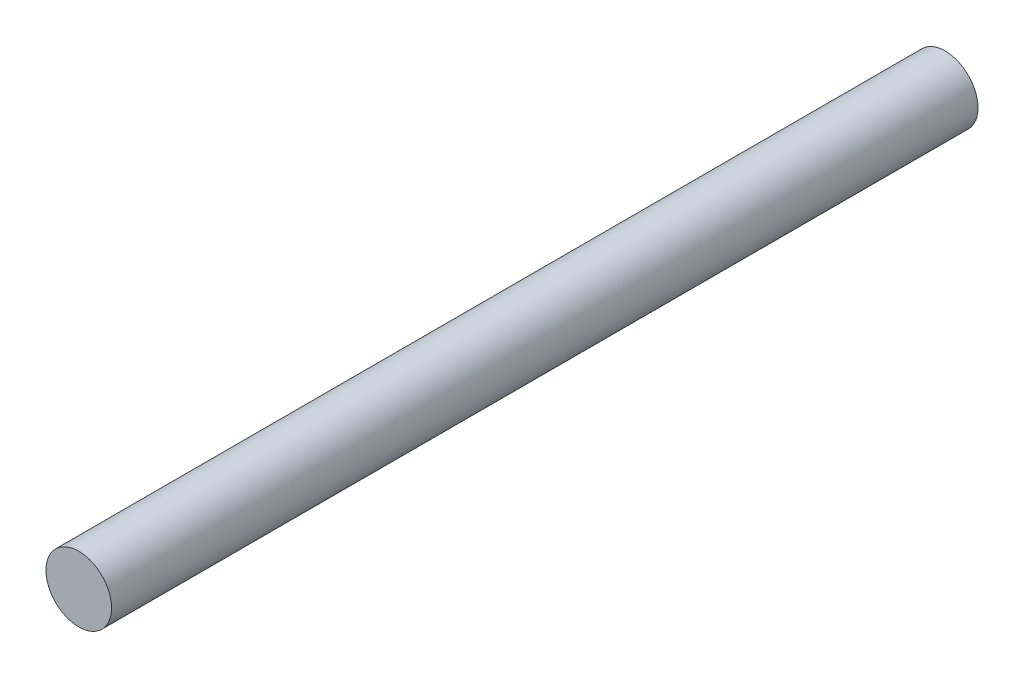
SolidWorks part; units mm, degrees
ref_plane "Front Plane" through (0, 0, 0) normal (0, 0, 1) x (1, 0, 0)
ref_plane "Top Plane" through (0, 0, 0) normal (0, 1, 0) x (1, 0, 0)
ref_plane "Right Plane" through (0, 0, 0) normal (1, 0, 0) x (0, 0, -1)
sketch "Sketch1" plane through (0, 0, 0) normal (0, 0, 1) x (1, 0, 0)
  circle A0 centre (0, 0) radius 2.5
  dimension "D1" = 5
extrude "Boss-Extrude1" add sketch "Sketch1" along normal blind 66
ref_point "Centre"
equation "\"StrutWidth\"= 15"
equation "\"D1@Boss-Extrude1\" = 5 * 2 + \"CarriageWidth\""
equation "\"CarriageWidth\"= 56"
